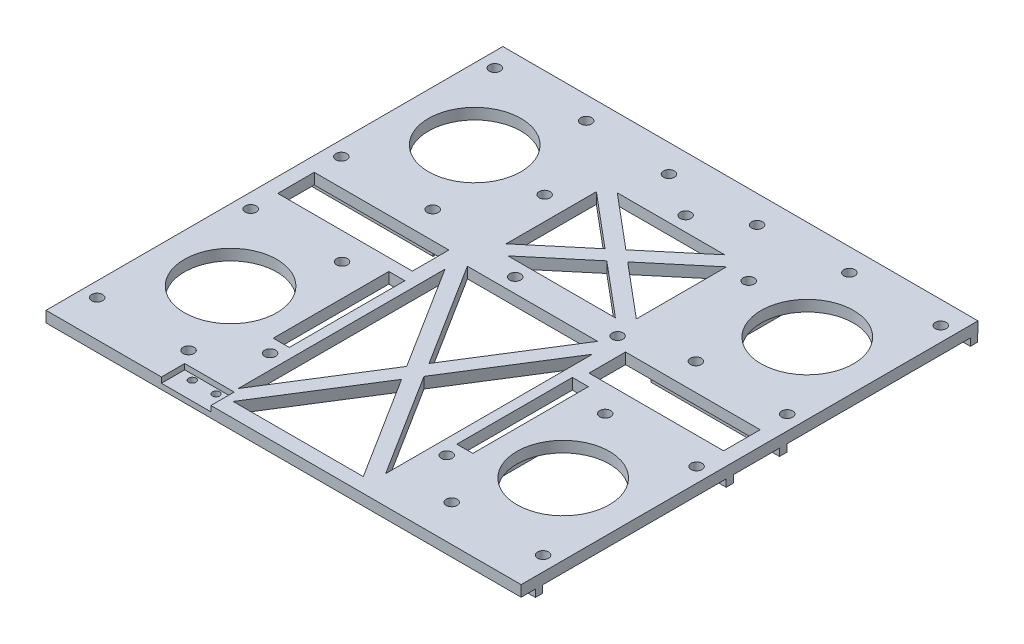
SolidWorks part; units mm, degrees
ref_plane "Front Plane" through (0, 0, 0) normal (0, 0, 1) x (1, 0, 0)
ref_plane "Top Plane" through (0, 0, 0) normal (0, 1, 0) x (1, 0, 0)
ref_plane "Right Plane" through (0, 0, 0) normal (1, 0, 0) x (0, 0, -1)
sketch "Sketch1" plane through (0, 0, 0) normal (0, 1, 0) x (1, 0, 0)
  line L1 (-65, 62.5) -> (65, 62.5)
  line L2 (-65, 62.5) -> (-65, -62.5)
  line L3 (-65, -62.5) -> (65, -62.5)
  line L4 (65, 62.5) -> (65, -62.5)
  line L5 (-65, 62.5) -> (65, -62.5) construction
  line L6 (-65, -62.5) -> (65, 62.5) construction
  point P0 (0, 0)
  dimension "D1" = 130
  dimension "D2" = 125
extrude "Boss-Extrude1" add sketch "Sketch1" along normal blind 5
sketch "Sketch2" plane through (0, 5, 0) normal (0, 1, 0) x (1, 0, 0)
  line L1 (-65, -62.5) -> (65, -62.5) construction
  line L2 (-65, 62.5) -> (-65, -62.5) construction
  circle A0 centre (-61, -52.5) radius 1.5
  circle A1 centre (-36, -52.5) radius 1.5
  circle A2 centre (-36, -10.5) radius 1.5
  circle A3 centre (-61, -10.5) radius 1.5
  circle A4 centre (-45.5, -31.5) radius 12.65
  dimension "D2" = 25.3
  dimension "D7" = 3
  dimension "D8" = 3
  dimension "D9" = 3
  dimension "D10" = 3
  dimension "D1" = 19.5
  dimension "D3" = 31
  dimension "D4" = 4
  dimension "D5" = 10
  dimension "D6" = 10
  dimension "D11" = 4
  dimension "D12" = 42
  dimension "D13" = 42
  dimension "D14" = 25
  dimension "D15" = 25
extrude "Cut-Extrude1" cut sketch "Sketch2" against normal blind 10
ref_plane "Plane1" through (0, 0, 0) normal (-1, 0, 0) x (0, 0, 1)
ref_plane "Plane2" through (0, 0, 0) normal (0, 0, 1) x (1, 0, 0)
mirror "Mirror3" about plane through (0, 0, 0) normal (-1, 0, 0) of "Cut-Extrude1"
sketch "Sketch4" plane through (0, 5, 0) normal (0, 1, 0) x (1, 0, 0)
  line L0 (0, 62.5) -> (0, 47.5) construction
  line L1 (65, 62.5) -> (-65, 62.5) construction
  line L2 (-12.0498, 55) -> (12.0498, 55) construction
  circle A0 centre (0, 47.5) radius 1.5
  circle A1 centre (12.0498, 55) radius 1.5
  circle A2 centre (-12.0498, 55) radius 1.5
  point P9 (0, 55)
  dimension "D2" = 3
  dimension "D3" = 3
  dimension "D4" = 3
  dimension "D1" = 15
  dimension "D5" = 24.0996
extrude "Cut-Extrude3" cut sketch "Sketch4" against normal blind 10
sketch "Sketch5" plane through (0, 0, 0) normal (0, -1, 0) x (1, 0, 0)
  line L0 (-58.15, 31.5) -> (-65, 31.5) construction
  line L1 (-65, -62.5) -> (-65, 62.5) construction
  line L2 (-65, 56.6) -> (-65, 6.4)
  line L3 (-65, 56.6) -> (-31.8, 56.6)
  line L4 (-31.8, 56.6) -> (-31.8, 6.4)
  line L5 (-31.8, 6.4) -> (-65, 6.4)
  line L6 (-65, 58.6) -> (-29.8, 58.6)
  line L7 (-29.8, 58.6) -> (-29.8, 4.4)
  line L8 (-29.8, 4.4) -> (-65, 4.4)
  line L9 (-65, 4.4) -> (-65, 6.4)
  line L10 (-65, 58.6) -> (-65, 56.6)
  circle A0 centre (-45.5, 31.5) radius 12.65 construction
  point P10 (-65, 31.5)
  line M39 (-65, 62.5) -> (-65, -62.5)
  dimension "D1" = 50.2
  dimension "D2" = 33.2
  dimension "D3" = 2
  dimension "D4" = 2
  dimension "D5" = 2
extrude "Boss-Extrude2" add sketch "Sketch5" along normal blind 2 contours L8 L7 L6 L3 L4 L5 M39
mirror "Mirror5" about plane through (0, 0, 0) normal (-1, 0, 0) of "Boss-Extrude2"
ref_plane "Plane3" through (0, 0, 0) normal (0, 0, 1) x (1, 0, 0)
ref_plane "Plane4" through (0, 0, -1.9) normal (0, 0, 1) x (1, 0, 0)
mirror "Mirror7" about plane through (0, 0, -1.9) normal (0, 0, 1) of "Mirror5", "Boss-Extrude2", "Mirror3", "Cut-Extrude1"
ref_plane "Plane5" through (0, 0, 0) normal (0, -1, 0) x (-1, 0, 0)
sketch "Sketch10" plane through (0, 0, 0) normal (0, -1, 0) x (-1, 0, 0)
  circle A0 centre (-24.17, -42.03) radius 1.5
  circle A1 centre (24.1662, -42.03) radius 1.5
  circle A2 centre (-19.2915, 9.5955) radius 1.5
  circle A3 centre (8.7247, 9.5955) radius 1.5
  circle A4 centre (-24.17, 40.5962) radius 1.5
  circle A5 centre (24.1662, 33.1032) radius 1.5
  circle A6 centre (-19.2915, 9.5955) radius 1.5621 construction
  circle A7 centre (8.7247, 9.5955) radius 1.3153 construction
  circle A8 centre (24.1662, 33.1032) radius 1.5621 construction
  circle A9 centre (-24.17, 40.5962) radius 1.5621 construction
  circle A10 centre (24.1662, -42.03) radius 1.5621 construction
  dimension "D1" = 3
  dimension "D6" = 3
  dimension "D7" = 3
  dimension "D10" = 3
  dimension "D11" = 3
  dimension "D12" = 3
extrude "Cut-Extrude8" cut sketch "Sketch10" against normal through all
sketch "Sketch11" plane through (0, 0, 0) normal (0, -1, 0) x (1, 0, 0)
  circle A0 centre (-12.0498, -55) radius 2.65
  circle A1 centre (0, -47.5) radius 2.65
  circle A2 centre (12.0498, -55) radius 2.65
  circle A3 centre (-24.1662, -33.1032) radius 2.65
  circle A4 centre (24.17, -40.5962) radius 2.65
  circle A5 centre (19.2915, -9.5955) radius 2.65
  circle A6 centre (-8.7247, -9.5955) radius 2.65
  circle A7 centre (-24.1662, 42.03) radius 2.65
  circle A8 centre (24.17, 42.03) radius 2.65
  circle A9 centre (-61, -14.3) radius 2.65
  circle A10 centre (-36, -14.3) radius 2.65
  circle A11 centre (-61, -56.3) radius 2.65
  circle A12 centre (-36, -56.3) radius 2.65
  circle A13 centre (36, -56.3) radius 2.65
  circle A14 centre (61, -56.3) radius 2.65
  circle A15 centre (36, -14.3) radius 2.65
  circle A16 centre (61, -14.3) radius 2.65
  circle A17 centre (36, 10.5) radius 2.65
  circle A18 centre (61, 10.5) radius 2.65
  circle A19 centre (61, 52.5) radius 2.65
  circle A20 centre (36, 52.5) radius 2.65
  circle A21 centre (-36, 52.5) radius 2.65
  circle A22 centre (-36, 10.5) radius 2.65
  circle A23 centre (-61, 10.5) radius 2.65
  circle A24 centre (-61, 52.5) radius 2.65
  dimension "D1" = 5.3
  dimension "D2" = 5.3
  dimension "D3" = 5.3
  dimension "D4" = 5.3
  dimension "D5" = 5.3
  dimension "D6" = 5.3
  dimension "D7" = 5.3
  dimension "D8" = 5.3
  dimension "D9" = 5.3
  dimension "D10" = 5.3
  dimension "D11" = 5.3
  dimension "D12" = 5.3
  dimension "D13" = 5.3
  dimension "D14" = 5.3
  dimension "D15" = 5.3
  dimension "D16" = 5.3
  dimension "D17" = 5.3
  dimension "D18" = 5.3
  dimension "D19" = 5.3
  dimension "D20" = 5.3
  dimension "D21" = 5.3
  dimension "D22" = 5.3
  dimension "D23" = 5.3
  dimension "D24" = 5.3
  dimension "D25" = 5.3
extrude "Cut-Extrude9" cut sketch "Sketch11" against normal blind 0.5
sketch "Sketch12" plane through (0, 5, 0) normal (0, 1, 0) x (1, 0, 0)
  line L0 (-65, -62.5) -> (65, -62.5) construction
  line L1 (-20.1662, 5.5955) -> (20.17, 5.5955)
  line L2 (-20.1662, 5.5955) -> (-20.1662, -58.5)
  line L3 (-20.1662, -58.5) -> (20.17, -58.5)
  line L4 (20.17, 5.5955) -> (20.17, -58.5)
  line L5 (-20.1662, 5.5955) -> (20.17, -58.5) construction
  line L6 (-20.1662, -58.5) -> (20.17, 5.5955) construction
  line L7 (-17.8031, 5.5955) -> (0.0019, -22.6972)
  line L8 (20.17, -54.745) -> (2.365, -26.4522)
  line L9 (2.365, -26.4522) -> (20.17, 1.8405)
  line L10 (0.0019, -22.6972) -> (17.8069, 5.5955)
  line L11 (-20.1662, 1.8405) -> (-2.3612, -26.4522)
  line L12 (-2.3612, -26.4522) -> (-20.1662, -54.745)
  line L13 (-17.8031, -58.5) -> (0.0019, -30.2073)
  line L14 (0.0019, -30.2073) -> (17.8069, -58.5)
  circle A0 centre (-8.7247, 9.5955) radius 1.5 construction
  circle A1 centre (-24.1662, -42.03) radius 1.5 construction
  circle A2 centre (24.17, -42.03) radius 1.5 construction
  dimension "D2" = 4
  dimension "D3" = 4
  dimension "D1" = 4
  dimension "D4" = 4
  dimension "D5" = 2
  dimension "D6" = 2
  dimension "D7" = 2
  dimension "D8" = 2
extrude "Cut-Extrude10" cut sketch "Sketch12" against normal through all contours L12 L11 L2 | L7 L10 L1 | L9 L8 L4 | L14 L13 L3
sketch "Sketch13" plane through (0, 5, 0) normal (0, 1, 0) x (1, 0, 0)
  line L0 (-61, 14.3) -> (-61, -10.5) construction
  line L1 (-61, 1.9) -> (-61, -3.1)
  line L2 (-61, -3.1) -> (-24.1662, -3.1)
  line L3 (-24.1662, -3.1) -> (-24.1662, 6.9)
  line L4 (-24.1662, 6.9) -> (-61, 6.9)
  line L5 (-61, 6.9) -> (-61, 1.9)
  line L6 (-20.1662, 1.8405) -> (-20.1662, -54.745) construction
  dimension "D1" = 10
  dimension "D2" = 5
  dimension "D3" = 4
extrude "Cut-Extrude11" cut sketch "Sketch13" against normal through all
mirror "Mirror9" about plane through (0, 0, 0) normal (-1, 0, 0) of "Cut-Extrude11"
sketch "Sketch14" plane through (0, 5, 0) normal (0, 1, 0) x (1, 0, 0)
  line L0 (-17.8031, 43.5) -> (17.8069, 13.5955) construction
  line L1 (-17.8031, 43.5) -> (17.8069, 43.5)
  line L2 (-17.8031, 43.5) -> (-17.8031, 13.5955)
  line L3 (-17.8031, 13.5955) -> (17.8069, 13.5955)
  line L4 (17.8069, 43.5) -> (17.8069, 13.5955)
  line L5 (-17.8031, 13.5955) -> (17.8069, 43.5) construction
  line L6 (-17.8031, 40.8883) -> (-3.1081, 28.5478)
  line L7 (-3.1081, 28.5478) -> (-17.8031, 16.2072)
  line L8 (-14.6931, 13.5955) -> (0.0019, 25.9361)
  line L9 (0.0019, 25.9361) -> (14.6969, 13.5955)
  line L10 (17.8069, 16.2072) -> (3.1119, 28.5478)
  line L11 (3.1119, 28.5478) -> (17.8069, 40.8883)
  line L12 (14.6969, 43.5) -> (0.0019, 31.1594)
  line L13 (0.0019, 31.1594) -> (-14.6931, 43.5)
  circle A0 centre (0, 47.5) radius 1.5 construction
  circle A1 centre (19.2915, 9.5955) radius 1.5 construction
  dimension "D1" = 4
  dimension "D2" = 4
  dimension "D3" = 2
  dimension "D4" = 2
  dimension "D5" = 2
  dimension "D6" = 2
  dimension "D7" = 2
  dimension "D8" = 2
  dimension "D9" = 2
  dimension "D10" = 2
extrude "Cut-Extrude12" cut sketch "Sketch14" against normal through all contours L7 L6 L2 | L13 L12 L1 | L11 L10 L4 | L9 L8 L3
sketch "Sketch15" plane through (0, 5, 0) normal (0, 1, 0) x (1, 0, 0)
  line L1 (-63.5, 58.8) -> (-58.5, 58.8)
  line L2 (-63.5, 58.8) -> (-63.5, 53.8)
  line L3 (-63.5, 53.8) -> (-58.5, 53.8)
  line L4 (65, -62.5) -> (65, 62.5)
  line L5 (65, 62.5) -> (-65, 62.5)
  line L6 (-65, 62.5) -> (-65, -62.5)
  line L7 (-65, -62.5) -> (65, -62.5)
  line L8 (65, -62.5) -> (65, 62.5)
  line L9 (65, 62.5) -> (-65, 62.5)
  line L10 (-65, 62.5) -> (-65, -62.5)
  line L11 (-65, -62.5) -> (65, -62.5)
  line L12 (-58.5, 58.8) -> (-58.5, 53.8)
  line L13 (-63.5, 58.8) -> (-58.5, 53.8) construction
  line L14 (-63.5, 53.8) -> (-58.5, 58.8) construction
  line L15 (-38.5, 58.8) -> (-33.5, 58.8)
  line L16 (-38.5, 58.8) -> (-38.5, 53.8)
  line L17 (-38.5, 53.8) -> (-33.5, 53.8)
  line L18 (-33.5, 58.8) -> (-33.5, 53.8)
  line L19 (-38.5, 58.8) -> (-33.5, 53.8) construction
  line L20 (-38.5, 53.8) -> (-33.5, 58.8) construction
  line L21 (-14.5498, 57.5) -> (-9.5498, 57.5)
  line L22 (-14.5498, 57.5) -> (-14.5498, 52.5)
  line L23 (-14.5498, 52.5) -> (-9.5498, 52.5)
  line L24 (-9.5498, 57.5) -> (-9.5498, 52.5)
  line L25 (-14.5498, 57.5) -> (-9.5498, 52.5) construction
  line L26 (-14.5498, 52.5) -> (-9.5498, 57.5) construction
  line L27 (-2.5, 50) -> (2.5, 50)
  line L28 (-2.5, 50) -> (-2.5, 45)
  line L29 (-2.5, 45) -> (2.5, 45)
  line L30 (2.5, 50) -> (2.5, 45)
  line L31 (-2.5, 50) -> (2.5, 45) construction
  line L32 (-2.5, 45) -> (2.5, 50) construction
  line L33 (9.5498, 57.5) -> (14.5498, 57.5)
  line L34 (9.5498, 57.5) -> (9.5498, 52.5)
  line L35 (9.5498, 52.5) -> (14.5498, 52.5)
  line L36 (14.5498, 57.5) -> (14.5498, 52.5)
  line L37 (9.5498, 57.5) -> (14.5498, 52.5) construction
  line L38 (9.5498, 52.5) -> (14.5498, 57.5) construction
  line L39 (33.5, 58.8) -> (38.5, 58.8)
  line L40 (33.5, 58.8) -> (33.5, 53.8)
  line L41 (33.5, 53.8) -> (38.5, 53.8)
  line L42 (38.5, 58.8) -> (38.5, 53.8)
  line L43 (33.5, 58.8) -> (38.5, 53.8) construction
  line L44 (33.5, 53.8) -> (38.5, 58.8) construction
  line L45 (63.5, 58.8) -> (58.5, 58.8)
  line L46 (63.5, 58.8) -> (63.5, 53.8)
  line L47 (63.5, 53.8) -> (58.5, 53.8)
  line L48 (58.5, 58.8) -> (58.5, 53.8)
  line L49 (63.5, 58.8) -> (58.5, 53.8) construction
  line L50 (63.5, 53.8) -> (58.5, 58.8) construction
  line L51 (33.5, 16.8) -> (38.5, 16.8)
  line L52 (33.5, 16.8) -> (33.5, 11.8)
  line L53 (33.5, 11.8) -> (38.5, 11.8)
  line L54 (38.5, 16.8) -> (38.5, 11.8)
  line L55 (33.5, 16.8) -> (38.5, 11.8) construction
  line L56 (33.5, 11.8) -> (38.5, 16.8) construction
  line L57 (63.5, 16.8) -> (58.5, 16.8)
  line L58 (63.5, 16.8) -> (63.5, 11.8)
  line L59 (63.5, 11.8) -> (58.5, 11.8)
  line L60 (58.5, 16.8) -> (58.5, 11.8)
  line L61 (63.5, 16.8) -> (58.5, 11.8) construction
  line L62 (63.5, 11.8) -> (58.5, 16.8) construction
  line L63 (21.67, 43.0962) -> (26.67, 43.0962)
  line L64 (21.67, 43.0962) -> (21.67, 38.0962)
  line L65 (21.67, 38.0962) -> (26.67, 38.0962)
  line L66 (26.67, 43.0962) -> (26.67, 38.0962)
  line L67 (21.67, 43.0962) -> (26.67, 38.0962) construction
  line L68 (21.67, 38.0962) -> (26.67, 43.0962) construction
  line L69 (33.5, -8) -> (38.5, -8)
  line L70 (33.5, -8) -> (33.5, -13)
  line L71 (33.5, -13) -> (38.5, -13)
  line L72 (38.5, -8) -> (38.5, -13)
  line L73 (33.5, -8) -> (38.5, -13) construction
  line L74 (33.5, -13) -> (38.5, -8) construction
  line L75 (63.5, -8) -> (58.5, -8)
  line L76 (63.5, -8) -> (63.5, -13)
  line L77 (63.5, -13) -> (58.5, -13)
  line L78 (58.5, -8) -> (58.5, -13)
  line L79 (63.5, -8) -> (58.5, -13) construction
  line L80 (63.5, -13) -> (58.5, -8) construction
  line L81 (21.67, -39.53) -> (26.67, -39.53)
  line L82 (21.67, -39.53) -> (21.67, -44.53)
  line L83 (21.67, -44.53) -> (26.67, -44.53)
  line L84 (26.67, -39.53) -> (26.67, -44.53)
  line L85 (21.67, -39.53) -> (26.67, -44.53) construction
  line L86 (21.67, -44.53) -> (26.67, -39.53) construction
  line L87 (38.5, -50) -> (33.5, -50)
  line L88 (38.5, -50) -> (38.5, -55)
  line L89 (38.5, -55) -> (33.5, -55)
  line L90 (33.5, -50) -> (33.5, -55)
  line L91 (38.5, -50) -> (33.5, -55) construction
  line L92 (38.5, -55) -> (33.5, -50) construction
  line L93 (63.5, -50) -> (58.5, -50)
  line L94 (63.5, -50) -> (63.5, -55)
  line L95 (63.5, -55) -> (58.5, -55)
  line L96 (58.5, -50) -> (58.5, -55)
  line L97 (63.5, -50) -> (58.5, -55) construction
  line L98 (63.5, -55) -> (58.5, -50) construction
  line L99 (-26.6662, -39.53) -> (-21.6662, -39.53)
  line L100 (-26.6662, -39.53) -> (-26.6662, -44.53)
  line L101 (-26.6662, -44.53) -> (-21.6662, -44.53)
  line L102 (-21.6662, -39.53) -> (-21.6662, -44.53)
  line L103 (-26.6662, -39.53) -> (-21.6662, -44.53) construction
  line L104 (-26.6662, -44.53) -> (-21.6662, -39.53) construction
  line L105 (-38.5, -50) -> (-33.5, -50)
  line L106 (-38.5, -50) -> (-38.5, -55)
  line L107 (-38.5, -55) -> (-33.5, -55)
  line L108 (-33.5, -50) -> (-33.5, -55)
  line L109 (-38.5, -50) -> (-33.5, -55) construction
  line L110 (-38.5, -55) -> (-33.5, -50) construction
  line L111 (-38.5, -8) -> (-33.5, -8)
  line L112 (-38.5, -8) -> (-38.5, -13)
  line L113 (-38.5, -13) -> (-33.5, -13)
  line L114 (-33.5, -8) -> (-33.5, -13)
  line L115 (-38.5, -8) -> (-33.5, -13) construction
  line L116 (-38.5, -13) -> (-33.5, -8) construction
  line L117 (16.7915, 12.0955) -> (21.7915, 12.0955)
  line L118 (16.7915, 12.0955) -> (16.7915, 7.0955)
  line L119 (16.7915, 7.0955) -> (21.7915, 7.0955)
  line L120 (21.7915, 12.0955) -> (21.7915, 7.0955)
  line L121 (16.7915, 12.0955) -> (21.7915, 7.0955) construction
  line L122 (16.7915, 7.0955) -> (21.7915, 12.0955) construction
  line L123 (-11.2247, 12.0955) -> (-6.2247, 12.0955)
  line L124 (-11.2247, 12.0955) -> (-11.2247, 7.0955)
  line L125 (-11.2247, 7.0955) -> (-6.2247, 7.0955)
  line L126 (-6.2247, 12.0955) -> (-6.2247, 7.0955)
  line L127 (-11.2247, 12.0955) -> (-6.2247, 7.0955) construction
  line L128 (-11.2247, 7.0955) -> (-6.2247, 12.0955) construction
  line L129 (-26.6662, 35.6032) -> (-21.6662, 35.6032)
  line L130 (-26.6662, 35.6032) -> (-26.6662, 30.6032)
  line L131 (-26.6662, 30.6032) -> (-21.6662, 30.6032)
  line L132 (-21.6662, 35.6032) -> (-21.6662, 30.6032)
  line L133 (-26.6662, 35.6032) -> (-21.6662, 30.6032) construction
  line L134 (-26.6662, 30.6032) -> (-21.6662, 35.6032) construction
  line L135 (-63.5, 16.8) -> (-58.5, 16.8)
  line L136 (-63.5, 16.8) -> (-63.5, 11.8)
  line L137 (-63.5, 11.8) -> (-58.5, 11.8)
  line L138 (-58.5, 16.8) -> (-58.5, 11.8)
  line L139 (-63.5, 16.8) -> (-58.5, 11.8) construction
  line L140 (-63.5, 11.8) -> (-58.5, 16.8) construction
  line L141 (-38.5, 16.8) -> (-33.5, 16.8)
  line L142 (-38.5, 16.8) -> (-38.5, 11.8)
  line L143 (-38.5, 11.8) -> (-33.5, 11.8)
  line L144 (-33.5, 16.8) -> (-33.5, 11.8)
  line L145 (-38.5, 16.8) -> (-33.5, 11.8) construction
  line L146 (-38.5, 11.8) -> (-33.5, 16.8) construction
  line L147 (-63.5, -8) -> (-58.5, -8)
  line L148 (-63.5, -8) -> (-63.5, -13)
  line L149 (-63.5, -13) -> (-58.5, -13)
  line L150 (-58.5, -8) -> (-58.5, -13)
  line L151 (-63.5, -8) -> (-58.5, -13) construction
  line L152 (-63.5, -13) -> (-58.5, -8) construction
  line L153 (-63.5, -50) -> (-58.5, -50)
  line L154 (-63.5, -50) -> (-63.5, -55)
  line L155 (-63.5, -55) -> (-58.5, -55)
  line L156 (-58.5, -50) -> (-58.5, -55)
  line L157 (-63.5, -50) -> (-58.5, -55) construction
  line L158 (-63.5, -55) -> (-58.5, -50) construction
  circle A0 centre (-61, 56.3) radius 1.5 construction
  circle A1 centre (-36, 56.3) radius 1.5 construction
  circle A2 centre (-12.0498, 55) radius 1.5 construction
  circle A3 centre (0, 47.5) radius 1.5 construction
  circle A4 centre (12.0498, 55) radius 1.5 construction
  circle A5 centre (36, 56.3) radius 1.5 construction
  circle A6 centre (61, 56.3) radius 1.5 construction
  circle A7 centre (24.17, 40.5962) radius 1.5 construction
  circle A8 centre (36, 14.3) radius 1.5 construction
  circle A9 centre (61, 14.3) radius 1.5 construction
  circle A10 centre (-24.1662, 33.1032) radius 1.5 construction
  circle A11 centre (-61, 14.3) radius 1.5 construction
  circle A12 centre (-36, 14.3) radius 1.5 construction
  circle A13 centre (-8.7247, 9.5955) radius 1.5 construction
  circle A14 centre (19.2915, 9.5955) radius 1.5 construction
  circle A15 centre (-61, -10.5) radius 1.5 construction
  circle A16 centre (-36, -10.5) radius 1.5 construction
  circle A17 centre (36, -10.5) radius 1.5 construction
  circle A18 centre (61, -10.5) radius 1.5 construction
  circle A19 centre (61, -52.5) radius 1.5 construction
  circle A20 centre (36, -52.5) radius 1.5 construction
  circle A21 centre (24.17, -42.03) radius 1.5 construction
  circle A22 centre (-24.1662, -42.03) radius 1.5 construction
  circle A23 centre (-36, -52.5) radius 1.5 construction
  circle A24 centre (-61, -52.5) radius 1.5 construction
  point P2 (-61, 56.3)
  point P12 (-36, 56.3)
  point P20 (-12.0498, 55)
  point P26 (0, 47.5)
  point P32 (12.0498, 55)
  point P38 (36, 56.3)
  point P44 (61, 56.3)
  point P50 (36, 14.3)
  point P56 (61, 14.3)
  point P62 (24.17, 40.5962)
  point P84 (36, -10.5)
  point P90 (61, -10.5)
  point P96 (24.17, -42.03)
  point P102 (36, -52.5)
  point P108 (61, -52.5)
  point P114 (-24.1662, -42.03)
  point P120 (-36, -52.5)
  point P126 (-36, -10.5)
  point P132 (19.2915, 9.5955)
  point P138 (-8.7247, 9.5955)
  point P144 (-24.1662, 33.1032)
  point P150 (-61, 14.3)
  point P156 (-36, 14.3)
  point P162 (-61, -10.5)
  point P168 (-61, -52.5)
  dimension "D2" = 2.5
  dimension "D3" = 2.5
  dimension "D4" = 2.5
  dimension "D5" = 2.5
  dimension "D6" = 2.5
  dimension "D7" = 2.5
  dimension "D8" = 2.5
  dimension "D9" = 2.5
  dimension "D10" = 2.5
  dimension "D11" = 2.5
  dimension "D12" = 2.5
  dimension "D13" = 2.5
  dimension "D15" = 2.5
  dimension "D16" = 2.5
  dimension "D17" = 2.5
  dimension "D18" = 2.5
  dimension "D19" = 2.5
  dimension "D20" = 2.5
  dimension "D21" = 2.5
  dimension "D22" = 2.5
  dimension "D23" = 2.5
  dimension "D24" = 2.5
  dimension "D25" = 2.5
  dimension "D26" = 2.5
  dimension "D27" = 2.5
  dimension "D28" = 2.5
  dimension "D29" = 2.5
  dimension "D30" = 2.5
  dimension "D31" = 2.5
  dimension "D32" = 2.5
  dimension "D33" = 2.5
  dimension "D34" = 2.5
  dimension "D35" = 2.5
  dimension "D36" = 2.5
  dimension "D37" = 2.5
  dimension "D38" = 2.5
  dimension "D39" = 2.5
  dimension "D40" = 2.5
  dimension "D41" = 2.5
  dimension "D42" = 2.5
  dimension "D43" = 2.5
  dimension "D44" = 2.5
  dimension "D45" = 2.5
  dimension "D46" = 2.5
  dimension "D47" = 2.5
  dimension "D48" = 2.5
  dimension "D49" = 2.5
  dimension "D14" = 2.5
  dimension "D1" = 0
extrude "Cut-Extrude14" cut sketch "Sketch15" against normal blind 2
ref_plane "Plane6" through (0, 13, 0) normal (0, 1, 0) x (1, 0, 0)
sketch "Sketch17" plane through (0, 13, 0) normal (0, 1, 0) x (1, 0, 0)
  line L1 (-68.0587, 64.2777) -> (69.5711, 64.2777)
  line L2 (-68.0587, 64.2777) -> (-68.0587, -66.7984)
  line L3 (-68.0587, -66.7984) -> (69.5711, -66.7984)
  line L4 (69.5711, 64.2777) -> (69.5711, -66.7984)
extrude "Cut-Extrude15" cut sketch "Sketch17" against normal blind 2 from surface at -8 starting at face at (-61, 5, -15.8)
sketch "Sketch18" plane through (0, 3, 0) normal (0, 1, 0) x (1, 0, 0)
  line L0 (-65, -62.5) -> (65, -62.5) construction
  line L1 (-33.412, -56.1297) -> (-19.8846, -56.1297)
  line L2 (-33.412, -56.1297) -> (-33.412, -62.5)
  line L3 (-33.412, -62.5) -> (-19.8846, -62.5)
  line L4 (-19.8846, -56.1297) -> (-19.8846, -62.5)
extrude "Cut-Extrude16" cut sketch "Sketch18" against normal blind 1.5
sketch "Sketch19" plane through (0, 1.5, 0) normal (0, 1, 0) x (1, 0, 0)
  circle A0 centre (-23.4163, -57.55) radius 1
  circle A1 centre (-29.9163, -57.55) radius 1
extrude "Cut-Extrude17" cut sketch "Sketch19" against normal blind 5
sketch "Sketch20" plane through (0, 0, 0) normal (0, -1, 0) x (1, 0, 0)
  line L1 (-32.8112, 59.7055) -> (-26.1535, 59.7055)
  line L2 (-32.8112, 59.7055) -> (-32.8112, 55.2822)
  line L3 (-32.8112, 55.2822) -> (-26.1535, 55.2822)
  line L4 (-26.1535, 59.7055) -> (-26.1535, 55.2822)
extrude "Cut-Extrude18" cut sketch "Sketch20" along normal up to surface (2 mm away) up to face at (-44.3916, -2, 36.71)
sketch "Sketch21" plane through (0, 0, 0) normal (0, -1, 0) x (-1, 0, 0)
  line L0 (-29.8, -58.6) -> (-29.8, -4.4) construction
  line L1 (-27.3, -6.4) -> (-22.9235, -6.4)
  line L2 (-27.3, -6.4) -> (-27.3, -38.03)
  line L3 (-27.3, -38.03) -> (-22.9235, -38.03)
  line L4 (-22.9235, -6.4) -> (-22.9235, -38.03)
  line L5 (22.9162, -6.4) -> (27.3, -6.4)
  line L6 (22.9162, -6.4) -> (22.9162, -38.03)
  line L7 (22.9162, -38.03) -> (27.3, -38.03)
  line L8 (27.3, -6.4) -> (27.3, -38.03)
  line L11 (29.8, -55.2822) -> (29.8, -4.4) construction
  line L12 (-20.17, 1.8405) -> (-20.17, -54.745) construction
  line L13 (20.1662, 1.8405) -> (20.1662, -54.745) construction
  line L14 (31.8, -6.4) -> (65, -6.4) construction
  circle A0 centre (-24.17, -42.03) radius 2.65 construction
  dimension "D5" = 4
  dimension "D1" = 2.5
  dimension "D2" = 2.5
  dimension "D3" = 2.7535
  dimension "D4" = 2.75
extrude "Cut-Extrude19" cut sketch "Sketch21" against normal blind 7.4
